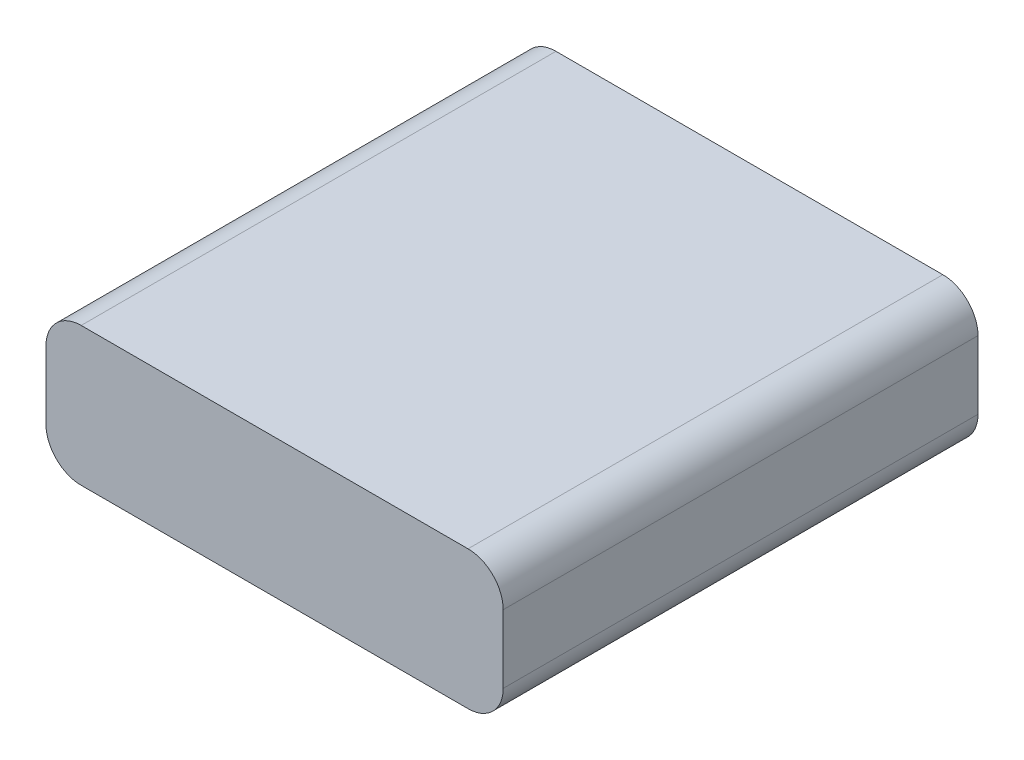
SolidWorks part; units mm, degrees
ref_plane "Front Plane" through (0, 0, 0) normal (0, 0, 1) x (1, 0, 0)
ref_plane "Top Plane" through (0, 0, 0) normal (0, 1, 0) x (1, 0, 0)
ref_plane "Right Plane" through (0, 0, 0) normal (1, 0, 0) x (0, 0, -1)
sketch "Sketch1" plane through (0, 0, 0) normal (0, 1, 0) x (1, 0, 0)
  line L1 (-33.02, 34.29) -> (33.02, 34.29)
  line L2 (-33.02, 34.29) -> (-33.02, -34.29)
  line L3 (-33.02, -34.29) -> (33.02, -34.29)
  line L4 (33.02, 34.29) -> (33.02, -34.29)
  line L5 (-33.02, 34.29) -> (33.02, -34.29) construction
  line L6 (-33.02, -34.29) -> (33.02, 34.29) construction
  point P0 (0, 0)
  dimension "D1" = 68.58
  dimension "D2" = 66.04
extrude "Extrude1" add sketch "Sketch1" along normal blind 20
fillet "Fillet1" radius 5.08 4 edges at (-33.02, 0, 0) (-33.02, 20, 0) (33.02, 0, 0) (33.02, 20, 0)
